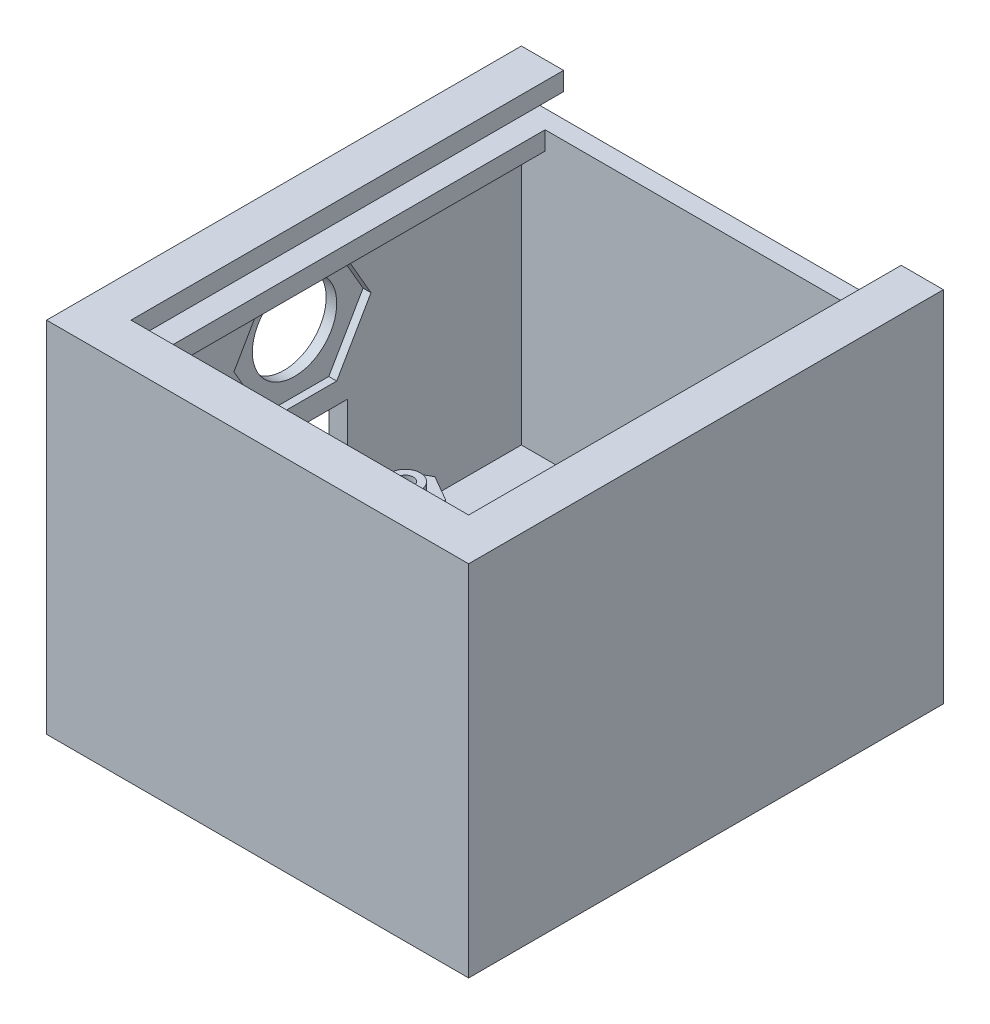
SolidWorks part; units mm, degrees
ref_plane "Front Plane" through (0, 0, 0) normal (0, 0, 1) x (1, 0, 0)
ref_plane "Top Plane" through (0, 0, 0) normal (0, 1, 0) x (1, 0, 0)
ref_plane "Right Plane" through (0, 0, 0) normal (1, 0, 0) x (0, 0, -1)
sketch "Sketch1" plane through (0, 0, 0) normal (0, 1, 0) x (1, 0, 0)
  line L1 (-40, -45) -> (40, -45)
  line L2 (-40, -45) -> (-40, 45)
  line L3 (-40, 45) -> (40, 45)
  line L4 (40, -45) -> (40, 45)
  line L5 (-40, -45) -> (40, 45) construction
  line L6 (-40, 45) -> (40, -45) construction
  point P0 (0, 0)
  dimension "D1" = 80
  dimension "D2" = 90
extrude "Boss-Extrude1" add sketch "Sketch1" along normal blind 6
sketch "Sketch4" plane through (0, 6, 0) normal (0, 1, 0) x (1, 0, 0)
  line L0 (40, -45) -> (40, 45) construction
  line L1 (-40, 45) -> (40, 45)
  line L2 (-40, 45) -> (-40, -45)
  line L3 (-40, -45) -> (40, -45)
  line L4 (40, 45) -> (40, -45)
  line L5 (-36.5, 41.5) -> (36.5, 41.5)
  line L6 (-36.5, 41.5) -> (-36.5, -41.5)
  line L7 (-36.5, -41.5) -> (36.5, -41.5)
  line L8 (36.5, 41.5) -> (36.5, -41.5)
  dimension "D1" = 3.5
  dimension "D2" = 3.5
  dimension "D3" = 3.5
  dimension "D4" = 3.5
extrude "Boss-Extrude2" add sketch "Sketch4" along normal blind 54 contours L2 L1 L4 L3 | L6 L5 L8 L7
sketch "Sketch5" plane through (0, 6, 0) normal (0, 1, 0) x (1, 0, 0)
  line L0 (-40, 45) -> (40, 45) construction
  line L1 (-36.5, 41.5) -> (-36.5, -41.5) construction
  line L2 (-36.5, 41.5) -> (-36.5, -41.5) construction
  circle A0 centre (-32.5, 15.5) radius 1.5
  circle A1 centre (-32.5, -15.5) radius 1.5
  dimension "D1" = 3
  dimension "D4" = 3
  dimension "D2" = 29.5
  dimension "D3" = 4
  dimension "D5" = 31
  dimension "D6" = 4
sketch "Sketch6" plane through (0, 6, 0) normal (0, 1, 0) x (1, 0, 0)
  line L0 (-40, 45) -> (-40, -45) construction
  line L1 (-40, 45) -> (40, 45) construction
  line L2 (-40, -45) -> (40, -45) construction
  line L3 (40, 45) -> (40, -45) construction
  circle A0 centre (-20, 25) radius 4.05
  circle A1 centre (-20, -25) radius 4.05
  circle A2 centre (20, -25) radius 5
  dimension "D2" = 8.1
  dimension "D3" = 8.1
  dimension "D4" = 20
  dimension "D5" = 20
  dimension "D8" = 10
  dimension "D1" = 20
  dimension "D6" = 20
  dimension "D7" = 20
extrude "Cut-Extrude1" cut sketch "Sketch6" against normal blind 40
sketch "Sketch7" plane through (0, 6, 0) normal (0, 1, 0) x (1, 0, 0)
  circle A0 centre (-20, 25) radius 7
  circle A1 centre (-20, -25) radius 7
  dimension "D1" = 14
  dimension "D2" = 14
extrude "Cut-Extrude2" cut sketch "Sketch7" against normal blind 2.8
sketch "Sketch8" plane through (0, 6, 0) normal (0, 1, 0) x (1, 0, 0)
  line L0 (-36.5, 41.5) -> (-36.5, -41.5) construction
  line L1 (-29.65, 17.1454) -> (-32.5, 18.7909)
  line L2 (-32.5, 18.7909) -> (-35.35, 17.1454)
  line L3 (-35.35, 17.1454) -> (-35.35, 13.8546)
  line L4 (-35.35, 13.8546) -> (-32.5, 12.2091)
  line L5 (-32.5, 12.2091) -> (-29.65, 13.8546)
  line L6 (-29.65, 13.8546) -> (-29.65, 17.1454)
  line L8 (-29.65, -13.8546) -> (-32.5, -12.2091)
  line L9 (-32.5, -12.2091) -> (-35.35, -13.8546)
  line L10 (-35.35, -13.8546) -> (-35.35, -17.1454)
  line L11 (-35.35, -17.1454) -> (-32.5, -18.7909)
  line L12 (-32.5, -18.7909) -> (-29.65, -17.1454)
  line L13 (-29.65, -17.1454) -> (-29.65, -13.8546)
  circle A0 centre (-32.5, 15.5) radius 2.85 construction
  circle A1 centre (-32.5, -15.5) radius 2.85 construction
  point P40 (-33.925, -13.0318)
  dimension "D1" = 5.7
  dimension "D4" = 5.7
sketch "Sketch10" plane through (0, 6, 0) normal (0, 1, 0) x (1, 0, 0)
  line L1 (-32.5, 21.1003) -> (-37.35, 18.3001)
  line L2 (-37.35, 18.3001) -> (-37.35, 12.6999)
  line L3 (-37.35, 12.6999) -> (-32.5, 9.8997)
  line L4 (-32.5, 9.8997) -> (-27.65, 12.6999)
  line L5 (-27.65, 12.6999) -> (-27.65, 18.3001)
  line L6 (-27.65, 18.3001) -> (-32.5, 21.1003)
  line L19 (-27.65, -12.6999) -> (-32.5, -9.8997)
  line L20 (-32.5, -9.8997) -> (-37.35, -12.6999)
  line L21 (-37.35, -12.6999) -> (-37.35, -18.3001)
  line L22 (-37.35, -18.3001) -> (-32.5, -21.1003)
  line L23 (-32.5, -21.1003) -> (-27.65, -18.3001)
  line L24 (-27.65, -18.3001) -> (-27.65, -12.6999)
  line L25 (-36.5, 41.5) -> (-36.5, -41.5) construction
  line L27 (-32.5, 12.2091) -> (-29.65, 13.8546) construction
  line L28 (-32.5, -18.7909) -> (-29.65, -17.1454) construction
  circle A0 centre (-32.5, 15.5) radius 4.85 construction
  circle A3 centre (-32.5, -15.5) radius 4.85 construction
  dimension "D1" = 2
  dimension "D2" = 2
extrude "Boss-Extrude3" add sketch "Sketch10" along normal blind 7
sketch "Sketch11" plane through (0, 13, 0) normal (0, 1, 0) x (1, 0, 0)
  circle A0 centre (-32.5, 15.5) radius 2.85
  circle A3 centre (-32.5, -15.5) radius 2.85
  dimension "D1" = 5.7
  dimension "D2" = 5.7
extrude "Boss-Extrude4" add sketch "Sketch11" along normal blind 2
extrude "Cut-Extrude3" cut sketch "Sketch5" against normal blind 6 and the other way blind 9
extrude "Cut-Extrude4" cut sketch "Sketch8" against normal through all and the other way blind 6
sketch "Sketch12" plane through (-36.5, 0, 0) normal (1, 0, 0) x (0, 0, -1)
  line L0 (45, 0) -> (-45, 0) construction
  line L1 (8.5, 16.5) -> (-8.5, 16.5)
  line L2 (8.5, 16.5) -> (8.5, 30)
  line L3 (8.5, 30) -> (-8.5, 30)
  line L4 (-8.5, 16.5) -> (-8.5, 30)
  line L5 (45, 60) -> (45, 0) construction
  dimension "D1" = 17
  dimension "D2" = 13.5
  dimension "16.5mm" = 16.5
  dimension "D4" = 36.5
extrude "Cut-Extrude6" cut sketch "Sketch12" against normal blind 3.5
sketch "Sketch15" plane through (-36.5, 0, 0) normal (1, 0, 0) x (0, 0, -1)
  line L0 (8.5, 30) -> (-8.5, 30) construction
  line L1 (-6.4952, 56.5) -> (-12.9904, 45.25)
  line L2 (-12.9904, 45.25) -> (-6.4952, 34)
  line L3 (-6.4952, 34) -> (6.4952, 34)
  line L4 (6.4952, 34) -> (12.9904, 45.25)
  line L5 (12.9904, 45.25) -> (6.4952, 56.5)
  line L6 (6.4952, 56.5) -> (-6.4952, 56.5)
  line L7 (45, 60) -> (45, 0) construction
  circle A1 centre (0, 45.25) radius 11.25 construction
  dimension "D1" = 22.5
  dimension "D2" = 45
  dimension "D3" = 4
sketch "Sketch17" plane through (-40, 0, 0) normal (-1, 0, 0) x (0, 0, 1)
  circle A0 centre (0, 45.25) radius 8
  dimension "D1" = 16
extrude "Cut-Extrude8" cut sketch "Sketch17" against normal blind 2
extrude "Cut-Extrude9" cut sketch "Sketch15" against normal blind 1.5
sketch "Sketch18" plane through (0, 15, 0) normal (0, 1, 0) x (1, 0, 0)
  line L1 (-35.5, 18.5) -> (-5.9, 18.5)
  line L2 (-35.5, 18.5) -> (-35.5, -19.1)
  line L3 (-35.5, -19.1) -> (-5.9, -19.1)
  line L4 (-5.9, 18.5) -> (-5.9, -19.1)
  circle A0 centre (-32.5, 15.5) radius 1.5 construction
  dimension "D1" = 3
  dimension "D2" = 3
  dimension "37.6" = 37.6
  dimension "D4" = 29.6
sketch "Sketch19" plane through (0, 6, 0) normal (0, 1, 0) x (1, 0, 0)
  line L0 (0, -5.5) -> (0, 5.5) construction
  line L1 (-3.5, -5.5) -> (-3.5, 5.5)
  line L2 (3.5, -5.5) -> (3.5, 5.5)
  line L3 (40, 45) -> (40, -45) construction
  line L5 (-40, -45) -> (40, -45) construction
  arc A0 (-3.5, -5.5) -> (3.5, -5.5) centre (0, -5.5) ccw
  arc A1 (3.5, 5.5) -> (-3.5, 5.5) centre (0, 5.5) ccw
  point P2 (0, 0)
  dimension "D1" = 40
  dimension "D2" = 45
  dimension "D3" = 11
  dimension "D4" = 7
extrude "Cut-Extrude10" cut sketch "Sketch19" against normal blind 10
sketch "Sketch20" plane through (0, 0, -45) normal (0, 0, -1) x (-1, 0, 0)
  line L0 (40, 60) -> (-40, 60) construction
  line L1 (-40, 60) -> (-36.5, 60)
  line L4 (-36.5, 60) -> (-36.5, 64.5)
  line L5 (40, 60) -> (36.5, 60)
  line L8 (36.5, 60) -> (36.5, 64.5)
  line L9 (-36.5, 64.5) -> (-32, 64.5)
  line L11 (-40, 68) -> (-32, 68)
  line L12 (-32, 64.5) -> (-32, 68)
  line L13 (36.5, 64.5) -> (32, 64.5)
  line L15 (40, 68) -> (32, 68)
  line L16 (32, 64.5) -> (32, 68)
  line L17 (-40, 68) -> (-40, 60)
  line L18 (40, 68) -> (40, 60)
  dimension "D1" = 8
  dimension "D2" = 3.5
  dimension "D3" = 3.5
  dimension "D4" = 3.5
  dimension "D5" = 3.5
  dimension "D7" = 8
  dimension "D8" = 8
extrude "Boss-Extrude5" add sketch "Sketch20" against normal blind 90 separate body
sketch "Sketch21" plane through (40, 0, 0) normal (1, 0, 0) x (0, 0, -1)
  line L0 (-45, 68) -> (45, 68) construction
  line L1 (-45, 60) -> (-41.5, 60)
  line L2 (-45, 60) -> (-45, 68)
  line L3 (-45, 68) -> (-41.5, 68)
  line L4 (-41.5, 60) -> (-41.5, 68)
  dimension "D1" = 3.5
extrude "Boss-Extrude6" add sketch "Sketch21" against normal blind 80
sketch "Sketch22" plane through (0, 0, 41.5) normal (0, 0, -1) x (-1, 0, 0)
  line L0 (-40, 68) -> (-40, 0) construction
  line L5 (40, 68) -> (-40, 68)
  line L6 (40, 68) -> (40, 64.5)
  line L7 (40, 64.5) -> (-40, 64.5)
  line L8 (-40, 68) -> (-40, 64.5)
  dimension "D1" = 3.5
extrude "Boss-Extrude7" add sketch "Sketch22" along normal blind 4.5
sketch "Sketch24" plane through (0, 0, 45) normal (0, 0, 1) x (1, 0, 0)
  line L0 (-40, 0) -> (-40, 68) construction
  line L1 (-40, 60) -> (-32, 60)
  line L2 (-40, 60) -> (-40, 56.5)
  line L3 (-40, 56.5) -> (-32, 56.5)
  line L4 (40, 60) -> (40, 56.5)
  line L5 (40, 68) -> (40, 0) construction
  line L6 (-40, 68) -> (40, 68) construction
  line L7 (32, 60) -> (40, 60)
  line L9 (-32, 60) -> (-32, 56.5)
  line L11 (32, 60) -> (32, 56.5)
  line L12 (32, 56.5) -> (40, 56.5)
  dimension "D1" = 3.5
  dimension "D2" = 8
  dimension "D3" = 8
  dimension "D4" = 8
extrude "Boss-Extrude8" add sketch "Sketch24" against normal blind 90
sketch "Sketch26" plane through (-40, 0, 0) normal (-1, 0, 0) x (0, 0, 1)
  line L0 (21.5, 40) -> (28.5, 40) construction
  line L1 (21.5, 42) -> (28.5, 42)
  line L2 (21.5, 38) -> (28.5, 38)
  line L3 (-45, 0) -> (45, 0) construction
  line L5 (45, 0) -> (45, 68) construction
  arc A0 (21.5, 42) -> (21.5, 38) centre (21.5, 40) ccw
  arc A1 (28.5, 38) -> (28.5, 42) centre (28.5, 40) ccw
  circle A2 centre (16.5, 40) radius 2
  circle A3 centre (33.5, 40) radius 2
  point P2 (25, 40)
  dimension "D4" = 4
  dimension "D5" = 4
  dimension "D1" = 5
  dimension "D2" = 5
  dimension "D3" = 7
  dimension "D6" = 40
  dimension "D7" = 20
  dimension "D8" = 4
extrude "Cut-Extrude11" cut sketch "Sketch26" against normal blind 3.5
